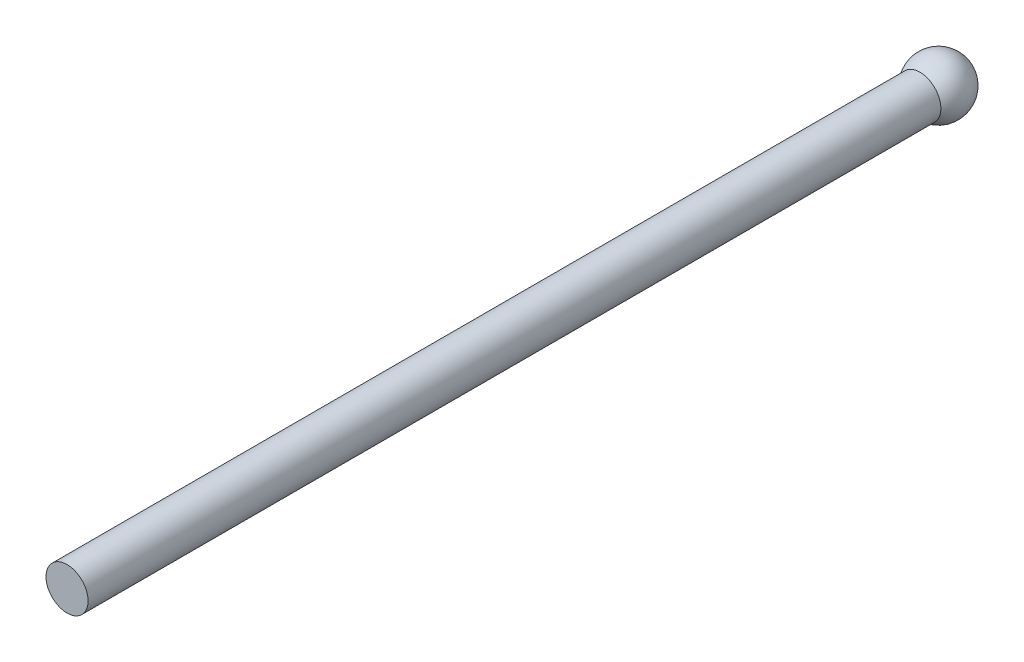
SolidWorks part; units mm, degrees
ref_plane "Front Plane" through (0, 0, 0) normal (0, 0, 1) x (1, 0, 0)
ref_plane "Top Plane" through (0, 0, 0) normal (0, 1, 0) x (1, 0, 0)
ref_plane "Right Plane" through (0, 0, 0) normal (1, 0, 0) x (0, 0, -1)
sketch "Sketch1" plane through (0, 0, 0) normal (0, 0, 1) x (1, 0, 0)
  circle A0 centre (0, 0) radius 7.5
  dimension "D1" = 15
extrude "Boss-Extrude1" add sketch "Sketch1" along normal blind 310.58 contours A0
sketch "Sketch2" plane through (0, 0, 0) normal (0, 1, 0) x (1, 0, 0)
  line L0 (0, 0) -> (0, 35.2643) construction
  line L2 (-7.5, 0) -> (-7.5, -310.58) construction
  line L4 (-7.5, -6.6144) -> (0, -6.6144)
  line L5 (0, -6.6144) -> (0, 10)
  arc A0 (-7.5, -6.6144) -> (0, 10) centre (0, 0) cw
  point P9 (-9.1144, 4.1144)
  dimension "D1" = 10
revolve "Revolve1" add sketch "Sketch2" angle 360 about L0
